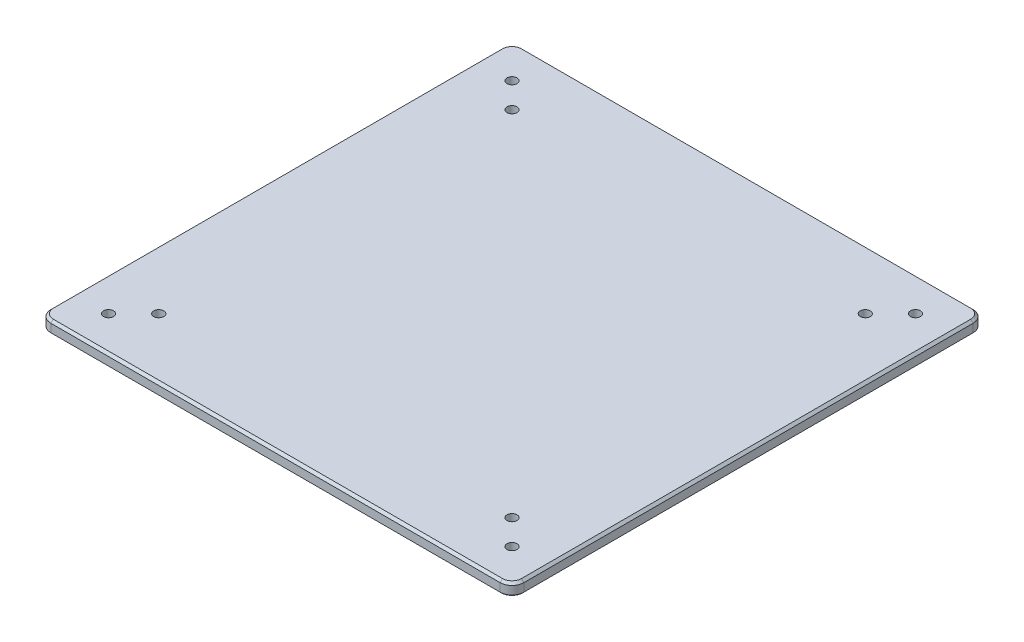
SolidWorks part; units mm, degrees
ref_plane "Front Plane" through (0, 0, 0) normal (0, 0, 1) x (1, 0, 0)
ref_plane "Top Plane" through (0, 0, 0) normal (0, 1, 0) x (1, 0, 0)
ref_plane "Right Plane" through (0, 0, 0) normal (1, 0, 0) x (0, 0, -1)
sketch "Sketch1" plane through (0, 0, 0) normal (0, 1, 0) x (1, 0, 0)
  line L1 (0, 0) -> (-200, 0)
  line L2 (0, 0) -> (0, -200)
  line L3 (0, -200) -> (-200, -200)
  line L4 (-200, 0) -> (-200, -200)
  dimension "D1" = 200
  dimension "D2" = 200
extrude "Boss-Extrude1" add sketch "Sketch1" along normal blind 5
sketch "Sketch2" plane through (0, 5, 0) normal (0, 1, 0) x (1, 0, 0)
  line L0 (-200, -200) -> (0, -200) construction
  line L2 (-200, 0) -> (0, -200) construction
  line L3 (-185.3033, -185.3033) -> (-174.6967, -174.6967) construction
  line L4 (-185.3033, -14.6926) -> (-174.6967, -25.2992) construction
  line L5 (-14.6926, -14.6926) -> (-25.2992, -25.2992) construction
  line L6 (-14.6926, -185.3033) -> (-25.2992, -174.6967) construction
  line L7 (-99.9979, -99.9979) -> (-174.6967, -174.6967) construction
  line L8 (-200, 0) -> (-200, -200) construction
  circle A0 centre (-185.3033, -185.3033) radius 2.125
  circle A1 centre (-174.6967, -174.6967) radius 2.125
  circle A2 centre (-185.3033, -14.6926) radius 2.125
  circle A3 centre (-174.6967, -25.2992) radius 2.125
  circle A4 centre (-14.6926, -14.6926) radius 2.125
  circle A5 centre (-25.2992, -25.2992) radius 2.125
  circle A6 centre (-14.6926, -185.3033) radius 2.125
  circle A7 centre (-25.2992, -174.6967) radius 2.125
  point P8 (-180, -180)
  dimension "D1" = 4.25
  dimension "D2" = 15
  dimension "D3" = 20
  dimension "D4" = 20
  dimension "D5" = 45
  dimension "D7" = 105.64
  dimension "D6" = 4
extrude "Cut-Extrude1" cut sketch "Sketch2" against normal through all
fillet "Fillet1" radius 5 4 edges at (-200, 2.5, 0) (0, 2.5, 0) (0, 2.5, 200) (-200, 2.5, 200)
chamfer "Chamfer1" distance 1 angle 45 8 edges at (0, 5, 100) (-1.4645, 5, 1.4645) (-1.4645, 5, 198.5355) (-100, 5, 0) (-100, 5, 200) (-198.5355, 5, 1.4645) (-198.5355, 5, 198.5355) (-200, 5, 100)
chamfer "Chamfer2" distance 0.5 angle 45 8 edges at (0, 0, 100) (-1.4645, 0, 1.4645) (-1.4645, 0, 198.5355) (-100, 0, 0) (-100, 0, 200) (-198.5355, 0, 1.4645) (-198.5355, 0, 198.5355) (-200, 0, 100)
